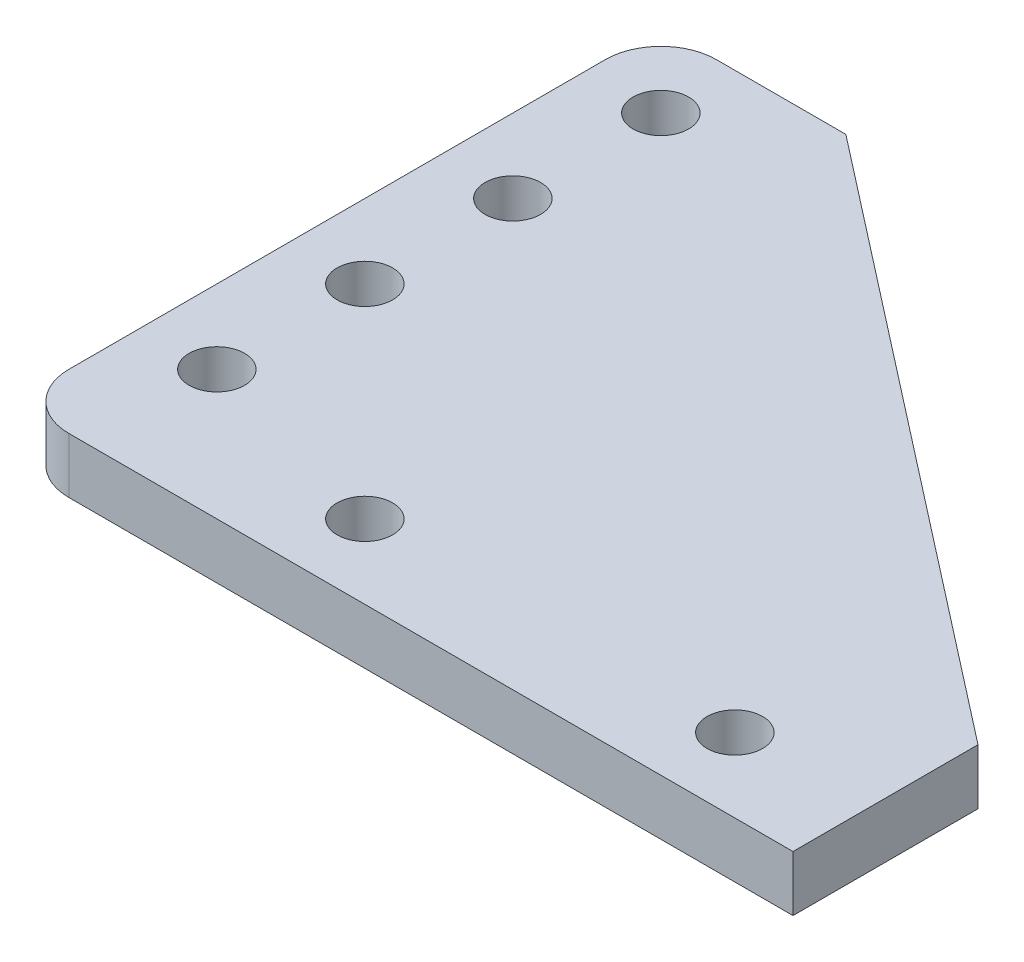
SolidWorks part; units mm, degrees
material "Thornel Mat VMA"
ref_plane "前视基准面" through (0, 0, 0) normal (0, 0, 1) x (1, 0, 0)
ref_plane "上视基准面" through (0, 0, 0) normal (0, 1, 0) x (1, 0, 0)
ref_plane "右视基准面" through (0, 0, 0) normal (1, 0, 0) x (0, 0, -1)
other "Configuration Table"
sketch "草图1" plane through (0, 0, 0) normal (0, 1, 0) x (1, 0, 0)
  line L0 (0, 0) -> (0, 57.832) construction
  line L1 (0, 0) -> (79.0599, 0) construction
  line L2 (0, -0.2283) -> (0, 35)
  line L3 (0, 35) -> (10, 35)
  line L4 (10, 35) -> (55, 0)
  line L5 (55, 0) -> (0, 0)
  line L7 (42.1429, 10) -> (42.1429, 0)
  circle A0 centre (4, 23) radius 1.5
  circle A1 centre (4, 15) radius 1.5
  circle A2 centre (15, 4) radius 1.5
  circle A3 centre (35, 4) radius 1.5
  circle A4 centre (4, 7) radius 1.5
  circle A5 centre (4, 31) radius 1.5
  dimension "D2" = 3
  dimension "D3" = 3
  dimension "D4" = 4
  dimension "D6" = 8
  dimension "D7" = 3
  dimension "D8" = 3
  dimension "D9" = 20
  dimension "D12" = 15
  dimension "D14" = 4
  dimension "D15" = 4
  dimension "D18" = 3
  dimension "D20" = 8
  dimension "D21" = 3
  dimension "D23" = 8
  dimension "D5" = 4
  dimension "D10" = 55
  dimension "D11" = 10
  dimension "D13" = 15
  dimension "D16" = 35
  dimension "D17" = 10
  dimension "D19" = 4
  dimension "D22" = 4
extrude "凸台-拉伸1" add sketch "草图1" along normal blind 3 contours L7 L4 L3 L2 L5 A3 A2 A1 A0
fillet "圆角1" radius 3 2 edges at (0, 1.5, 0) (0, 1.5, -35)
